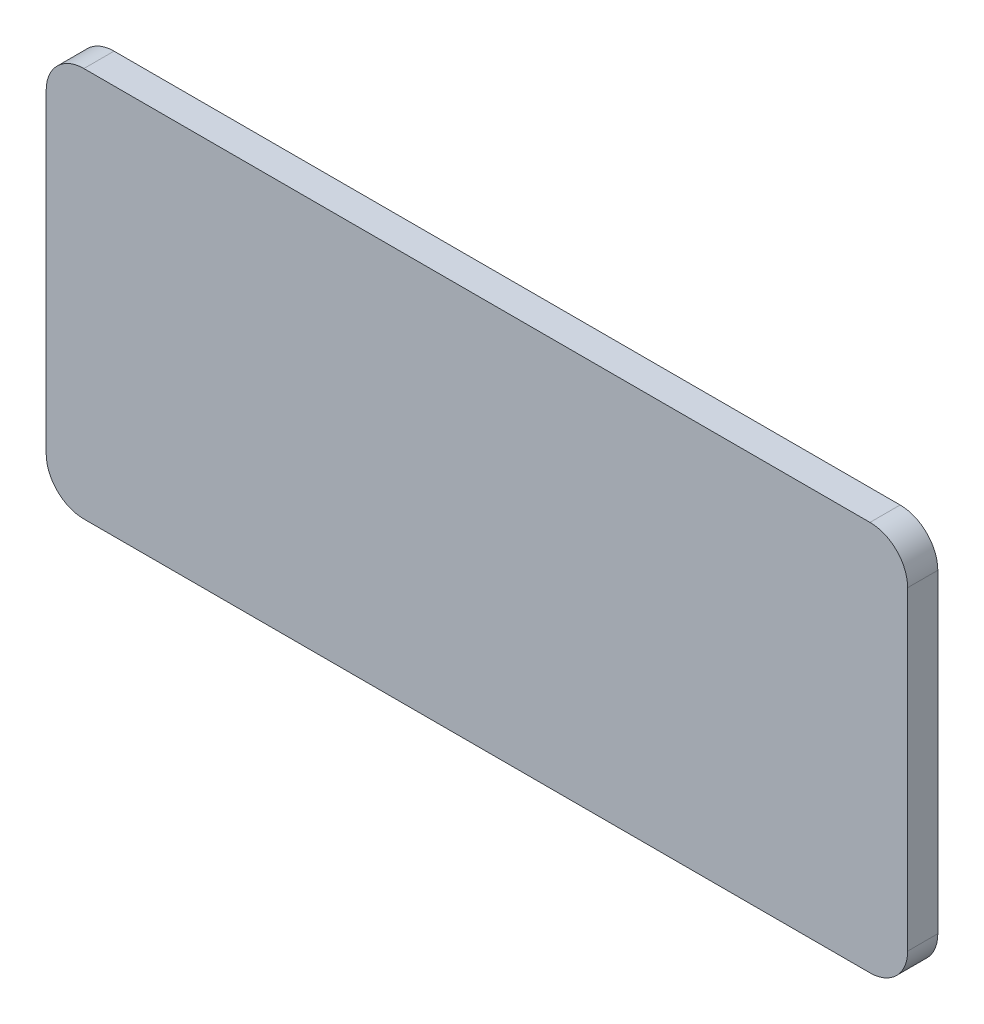
SolidWorks part; units mm, degrees
ref_plane "Front" through (0, 0, 0) normal (0, 0, 1) x (1, 0, 0)
ref_plane "Top" through (0, 0, 0) normal (0, 1, 0) x (1, 0, 0)
ref_plane "Right" through (0, 0, 0) normal (1, 0, 0) x (0, 0, -1)
sketch "Esquisse1" plane through (0, 0, 0) normal (0, 0, 1) x (1, 0, 0)
  line L1 (-22.855, 10.35) -> (22.855, 10.35)
  line L2 (-22.855, 10.35) -> (-22.855, -10.35)
  line L3 (-22.855, -10.35) -> (22.855, -10.35)
  line L4 (22.855, 10.35) -> (22.855, -10.35)
  dimension "D1" = 45.71
  dimension "D2" = 20.7
  dimension "D3" = 22.855
  dimension "D4" = 10.35
extrude "Boss.-Extru.1" add sketch "Esquisse1" along normal blind 1.6
fillet "Congé1" radius 2 4 edges at (-22.855, -10.35, 0.8) (22.855, -10.35, 0.8) (22.855, 10.35, 0.8) (-22.855, 10.35, 0.8)
